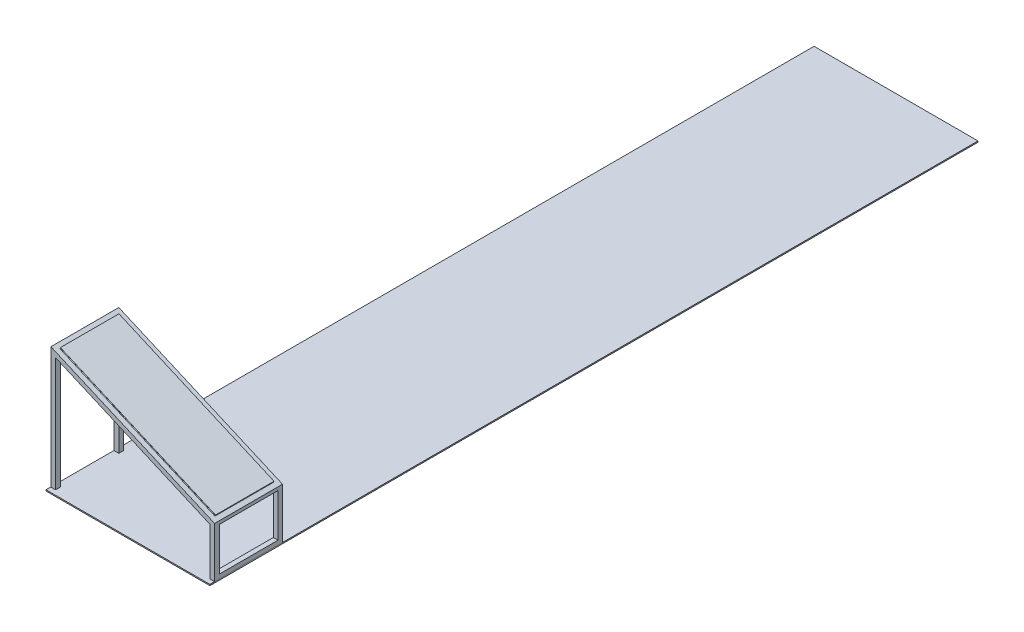
SolidWorks part; units mm, degrees
ref_plane "前基準面" through (0, 0, 0) normal (0, 0, 1) x (1, 0, 0)
ref_plane "上基準面" through (0, 0, 0) normal (0, 1, 0) x (1, 0, 0)
ref_plane "右基準面" through (0, 0, 0) normal (1, 0, 0) x (0, 0, -1)
sketch "草圖1" plane through (0, 0, 0) normal (0, 0, 1) x (1, 0, 0)
  line L1 (0, 0) -> (1400, 0)
  line L2 (0, 0) -> (0, 10)
  line L3 (0, 10) -> (1400, 10)
  line L4 (1400, 0) -> (1400, 10)
  dimension "D1" = 1400
  dimension "D2" = 10
extrude "填料-伸長1" add sketch "草圖1" against normal blind 6560
sketch "草圖2" plane through (0, 0, 0) normal (0, 0, 1) x (1, 0, 0)
  line L0 (1400, 440.7493) -> (299.5279, 919.2482)
  line L1 (1.7506, 882.5658) -> (1.7506, 10) construction
  line L2 (41.7506, 987.7153) -> (1360, 414.5242)
  line L4 (1400, 0) -> (1400, 10) construction
  line L5 (1400, 440.7493) -> (1400, 10)
  line L6 (1400, 10) -> (1360, 10)
  line L7 (1400, 10) -> (0, 10) construction
  line L8 (1360, 10) -> (1360, 414.5242)
  line L9 (1.7506, 1048.7255) -> (1.7506, 10)
  line L10 (41.7506, 987.7153) -> (41.7506, 10)
  line L11 (1.7506, 10) -> (41.7506, 10)
  line L12 (41.7506, 10) -> (322.4181, 200.7455)
  line L13 (41.7506, 882.5658) -> (41.7506, 10) construction
  line L17 (299.5279, 919.2482) -> (1.7506, 1048.7255)
  line M4 (1400, 10) -> (0, 10)
  dimension "D2" = 40
  dimension "D3" = 40
  dimension "D4" = 23.5
  dimension "D1" = 40
extrude "填料-伸長2" add sketch "草圖2" against normal blind 580 from offset 40 separate body contours L0 L17 L9 L10 L2 L8 L5 M4 offset against normal yes
sketch "草圖3" plane through (383.773, 882.6174, 0) normal (0.3987, 0.9171, 0) x (0.9171, -0.3987, 0)
  line L0 (-376.5729, 580) -> (1068.1357, 580)
  line L1 (1068.1357, 580) -> (1068.1357, 80)
  line L2 (1068.1357, 80) -> (-376.5729, 80)
  line L3 (-376.5729, 80) -> (-376.5729, 580)
  line L4 (1108.1357, 620) -> (-416.5729, 620) construction
  line L5 (1108.1357, 40) -> (-416.5729, 40) construction
  line L6 (-416.5729, 620) -> (-416.5729, 40) construction
  line L7 (1108.1357, 620) -> (1108.1357, 40) construction
  dimension "D1" = 40
  dimension "D2" = 40
  dimension "D3" = 40
  dimension "D4" = 40
extrude "除料-伸長2" cut sketch "草圖3" against normal up to next
sketch "草圖4" plane through (1400, 0, 0) normal (1, 0, 0) x (0, 0, -1)
  line L0 (83.8787, 413.0742) -> (83.8787, 45.8929)
  line L1 (83.8787, 45.8929) -> (581.4873, 45.8929)
  line L2 (581.4873, 45.8929) -> (581.4873, 413.0742)
  line L3 (581.4873, 413.0742) -> (83.8787, 413.0742)
  line L4 (83.8787, 413.0742) -> (83.8787, 414.4919)
extrude "除料-伸長3" cut sketch "草圖4" against normal blind 230 contours L2 L3 L0 L1
sketch "草圖5" plane through (41.7506, 0, 0) normal (1, 0, 0) x (0, 0, -1)
  line L0 (580, 1008.7255) -> (580, 50)
  line L1 (580, 50) -> (80, 50)
  line L2 (80, 50) -> (80, 1008.7255)
  line L3 (80, 1008.7255) -> (580, 1008.7255)
  line L4 (620, 1048.7255) -> (620, 10) construction
  line L5 (620, 10) -> (580, 10) construction
  line L6 (620, 1048.7255) -> (40, 1048.7255) construction
  line L7 (40, 1048.7255) -> (40, 10) construction
  dimension "D1" = 40
  dimension "D2" = 40
  dimension "D3" = 40
  dimension "D4" = 40
extrude "除料-伸長5" cut sketch "草圖5" against normal blind 103
ref_plane "平面1" through (387.7605, 891.788, 0) normal (0.3987, 0.9171, 0) x (0.9171, -0.3987, 0)
sketch "草圖6" plane through (387.7605, 891.788, 0) normal (0.3987, 0.9171, 0) x (0.9171, -0.3987, 0)
  line L0 (1068.1357, 580) -> (-376.5729, 580) construction
  line L1 (-376.5729, 80) -> (1068.1357, 80)
  line L2 (-376.5729, 80) -> (-376.5729, 580)
  line L3 (-376.5729, 580) -> (1068.1357, 580)
  line L4 (1068.1357, 80) -> (1068.1357, 580)
  line L5 (1068.1357, 80) -> (1068.1357, 580) construction
extrude "填料-伸長3" add sketch "草圖6" along normal blind 1 separate body
